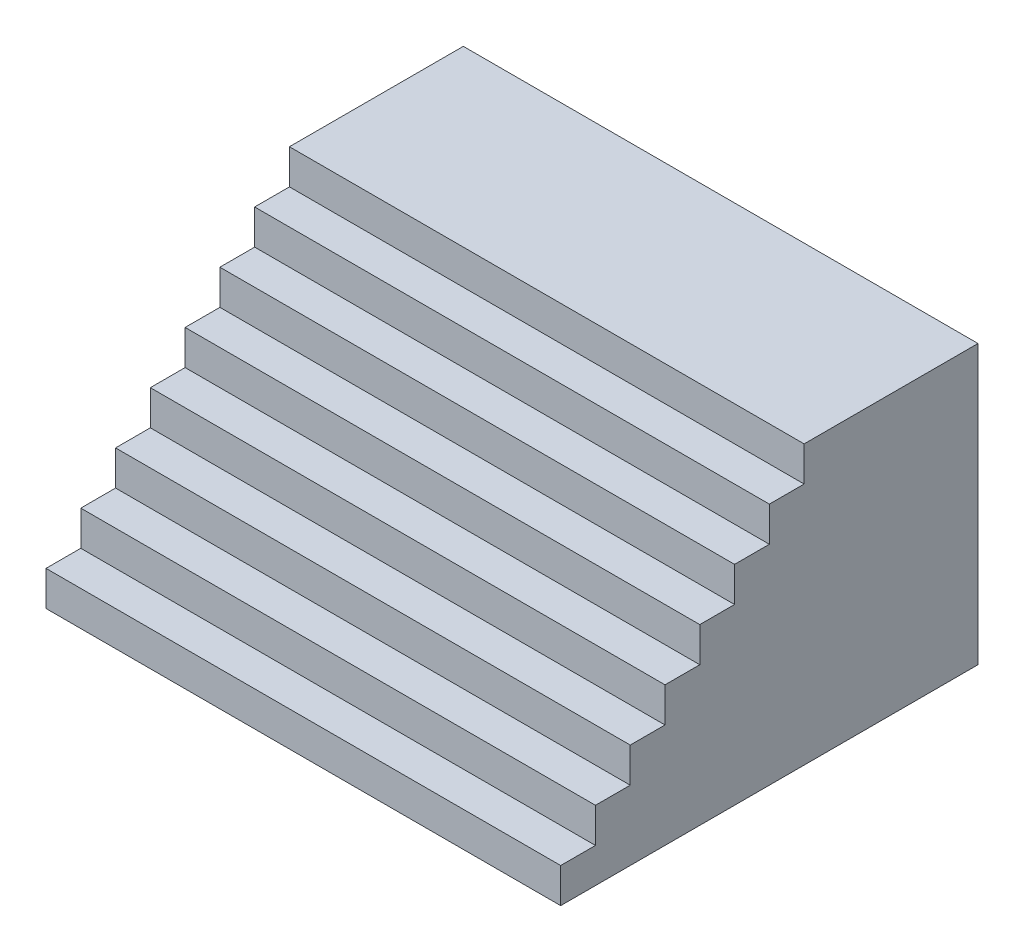
SolidWorks part; units mm, degrees
material "6061 Alloy"
ref_plane "Front Plane" through (0, 0, 0) normal (0, 0, 1) x (1, 0, 0)
ref_plane "Top Plane" through (0, 0, 0) normal (0, 1, 0) x (1, 0, 0)
ref_plane "Right Plane" through (0, 0, 0) normal (1, 0, 0) x (0, 0, -1)
sketch3d "3DSketch3"
  line L0 (0, 0, 0) -> (0, 0, 2783.3008) construction
  line L1 (-1850, 1000, 0) -> (1850, 1000, 0)
  line L2 (-1850, 1000, 0) -> (-1850, -1000, 0)
  line L3 (-1850, -1000, 0) -> (1850, -1000, 0)
  line L4 (1850, 1000, 0) -> (1850, -1000, 0)
  line L5 (-1850, 1000, 0) -> (1850, -1000, 0) construction
  line L6 (-1850, -1000, 0) -> (1850, 1000, 0) construction
  point P0 (0, 0, 0)
  dimension "D1" = 2000
  dimension "D2" = 3700
extrude "Boss-Extrude2" add sketch "3DSketch3" along direction (0, 0, 1) on the side of the normal blind 3000
sketch "Sketch4" plane through (-1850, 0, 0) normal (-1, 0, 0) x (0, 0, 1)
  line L1 (3000, -1000) -> (3000, 1000) construction
  line L2 (3000, -750) -> (2750, -750)
  line L3 (2750, -750) -> (2750, -500)
  line L4 (2750, -500) -> (2500, -500)
  line L5 (2500, -500) -> (2500, -250)
  line L6 (2500, -250) -> (2250, -250)
  line L7 (2250, -250) -> (2250, 0)
  line L8 (2250, 0) -> (2000, 0)
  line L9 (2000, 0) -> (2000, 250)
  line L10 (2000, 250) -> (1750, 250)
  line L11 (1750, 250) -> (1750, 500)
  line L12 (1750, 500) -> (1500, 500)
  line L13 (1500, 500) -> (1500, 750)
  line L14 (1500, 750) -> (1250, 750)
  line L15 (1250, 750) -> (1250, 1000)
  line L16 (0, 1000) -> (3000, 1000) construction
  line L17 (1250, 1000) -> (3000, 1000)
  line L18 (3000, 1000) -> (3000, -750)
  dimension "D2" = 250
  dimension "D3" = 250
  dimension "D4" = 250
  dimension "D5" = 250
  dimension "D6" = 250
  dimension "D7" = 250
  dimension "D8" = 250
  dimension "D9" = 250
  dimension "D10" = 250
  dimension "D11" = 250
  dimension "D12" = 250
  dimension "D13" = 250
extrude "Cut-Extrude1" cut sketch "Sketch4" against normal blind 4000
